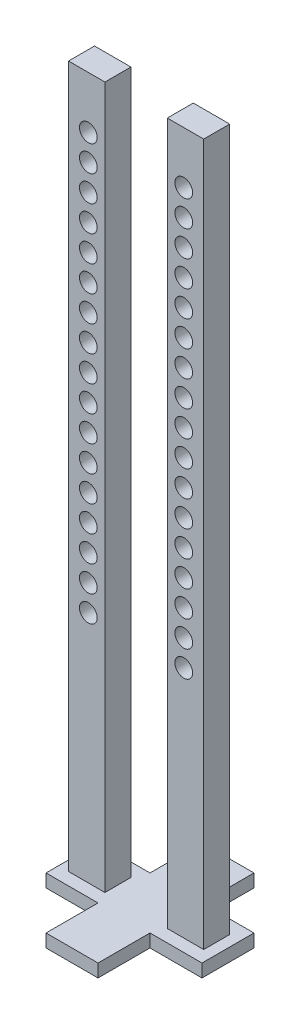
SolidWorks part; units mm, degrees
ref_plane "Front Plane" through (0, 0, 0) normal (0, 0, 1) x (1, 0, 0)
ref_plane "Top Plane" through (0, 0, 0) normal (0, 1, 0) x (1, 0, 0)
ref_plane "Right Plane" through (0, 0, 0) normal (1, 0, 0) x (0, 0, -1)
sketch "Sketch1" plane through (0, 0, 0) normal (0, 1, 0) x (1, 0, 0)
  line L0 (4.2105, 15) -> (-5.7895, 15)
  line L1 (-5.7895, 15) -> (-5.7895, 5)
  line L2 (-5.7895, 5) -> (-15.7895, 5)
  line L3 (-15.7895, 5) -> (-15.7895, -5)
  line L4 (-23.9474, 0) -> (25.2632, 0) construction
  line L5 (-5.7895, -5) -> (-15.7895, -5)
  line L6 (-5.7895, -15) -> (-5.7895, -5)
  line L7 (4.2105, -15) -> (-5.7895, -15)
  line L8 (-0.7895, 31.0526) -> (-0.7895, -24.7368) construction
  line L9 (4.2105, -15) -> (4.2105, -5)
  line L10 (4.2105, -5) -> (14.2105, -5)
  line L11 (14.2105, 5) -> (14.2105, -5)
  line L12 (4.2105, 5) -> (14.2105, 5)
  line L13 (4.2105, 15) -> (4.2105, 5)
  point P9 (-15.7895, 0)
  point P14 (14.2105, 0)
  point P16 (-0.7895, -15)
  point P21 (-0.7895, 15)
  dimension "D1" = 5
  dimension "D2" = 5
  dimension "D3" = 10
  dimension "D4" = 10
extrude "Boss-Extrude1" add sketch "Sketch1" against normal blind 2.5
sketch "Sketch3" plane through (0, 0, 0) normal (0, 1, 0) x (1, 0, 0)
  line L6 (-13.8653, -2.595) -> (-6.8653, -2.595)
  line L7 (-13.8653, -2.595) -> (-13.8653, 2.405)
  line L8 (-13.8653, 2.405) -> (-6.8653, 2.405)
  line L9 (-6.8653, -2.595) -> (-6.8653, 2.405)
  line L10 (-13.8653, -2.595) -> (-6.8653, 2.405) construction
  line L11 (-13.8653, 2.405) -> (-6.8653, -2.595) construction
  line L12 (5.1347, -2.595) -> (12.1347, -2.595)
  line L13 (5.1347, -2.595) -> (5.1347, 2.405)
  line L14 (5.1347, 2.405) -> (12.1347, 2.405)
  line L15 (12.1347, -2.595) -> (12.1347, 2.405)
  line L16 (5.1347, -2.595) -> (12.1347, 2.405) construction
  line L17 (5.1347, 2.405) -> (12.1347, -2.595) construction
  point P0 (-10.3653, -0.095)
  point P5 (8.6347, -0.095)
  dimension "D1" = 7
  dimension "D2" = 5
  dimension "D3" = 12
  dimension "D4" = 7
  dimension "D5" = 5
  dimension "D6" = 0
extrude "Boss-Extrude2" add sketch "Sketch3" along normal blind 135
sketch "Sketch4" plane through (0, 0, 0) normal (0, 0, 1) x (1, 0, 0)
  line L0 (-13.8653, 135) -> (-6.8653, 135) construction
  line L1 (5.1347, 135) -> (12.1347, 135) construction
  circle A0 centre (-10.0595, 125) radius 1.705
  circle A1 centre (8.2952, 125) radius 1.705
  dimension "D1" = 3.41
  dimension "D2" = 3.41
  dimension "D4" = 10
  dimension "D3" = 10
extrude "Cut-Extrude1" cut sketch "Sketch4" along normal mid plane 10
pattern_linear "LPattern1" count 17 spacing 5 along (0, -1, 0) of "Cut-Extrude1"
